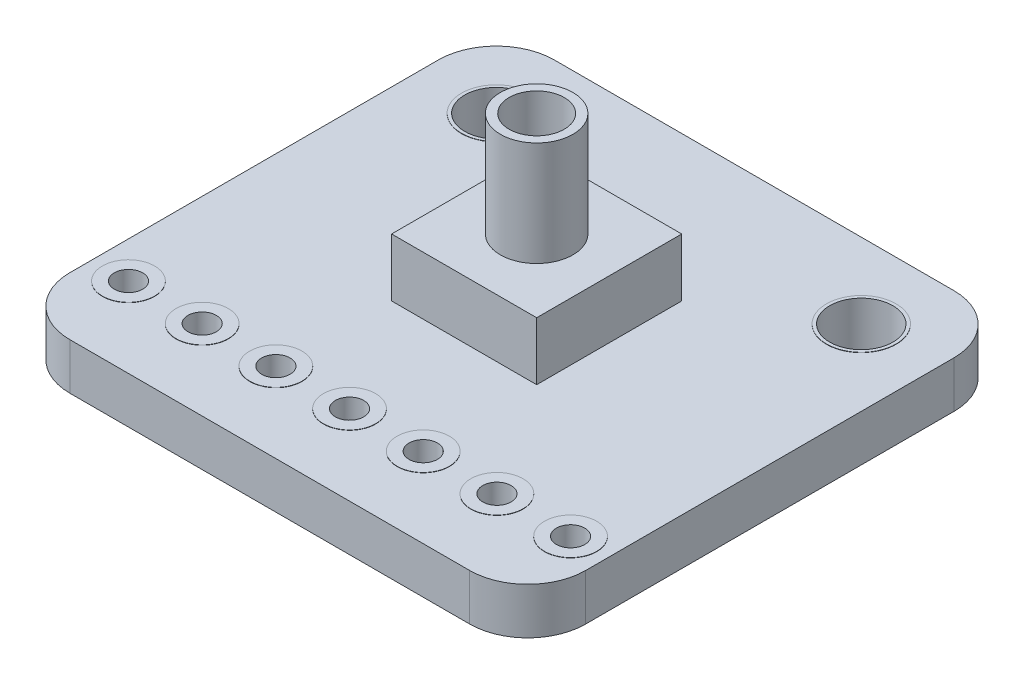
SolidWorks part; units mm, degrees
ref_plane "Front Plane" through (0, 0, 0) normal (0, 0, 1) x (1, 0, 0)
ref_plane "Top Plane" through (0, 0, 0) normal (0, 1, 0) x (1, 0, 0)
ref_plane "Right Plane" through (0, 0, 0) normal (1, 0, 0) x (0, 0, -1)
sketch "Sketch1" plane through (0, 0, 0) normal (0, 1, 0) x (1, 0, 0)
  line L1 (-6.89, 8.35) -> (6.89, 8.35)
  line L2 (-8.89, 6.35) -> (-8.89, -6.35)
  line L3 (-6.89, -8.35) -> (6.89, -8.35)
  line L4 (8.89, 6.35) -> (8.89, -6.35)
  line L5 (-8.89, 8.35) -> (8.89, -8.35) construction
  line L6 (-8.89, -8.35) -> (8.89, 8.35) construction
  arc A0 (-8.89, -6.35) -> (-6.89, -8.35) centre (-6.89, -6.35) ccw
  arc A1 (6.89, -8.35) -> (8.89, -6.35) centre (6.89, -6.35) ccw
  arc A2 (6.89, 8.35) -> (8.89, 6.35) centre (6.89, 6.35) cw
  arc A3 (-6.89, 8.35) -> (-8.89, 6.35) centre (-6.89, 6.35) ccw
  point P0 (0, 0)
  dimension "D3" = 2
  dimension "D1" = 17.78
  dimension "D2" = 16.7
extrude "Boss-Extrude1" add sketch "Sketch1" along normal blind 1.6
sketch "Sketch2" plane through (0, 1.6, 0) normal (0, 1, 0) x (1, 0, 0)
  line L0 (0, 0) -> (0, 8.35) construction
  line L1 (-8.89, -8.35) -> (8.89, 8.35) construction
  line L2 (-6.89, 8.35) -> (6.89, 8.35) construction
  line L3 (-6.89, -8.35) -> (6.89, -8.35) construction
  line L4 (-8.89, -4.33) -> (8.89, -4.33) construction
  line L5 (-8.89, -4.33) -> (-8.89, -6.87) construction
  line L6 (-8.89, -6.87) -> (8.89, -6.87) construction
  line L7 (8.89, -4.33) -> (8.89, -6.87) construction
  line L8 (-8.89, -4.33) -> (8.89, -6.87) construction
  line L9 (-8.89, -6.87) -> (8.89, -4.33) construction
  line L10 (-8.89, 6.35) -> (-8.89, -6.35) construction
  line L11 (8.89, 6.35) -> (8.89, -6.35) construction
  line L12 (6.89, 8.35) -> (-6.89, 8.35) construction
  circle A0 centre (-6.29, 5.75) radius 1.1
  circle A1 centre (6.29, 5.75) radius 1.1
  circle A2 centre (-7.62, -5.6) radius 0.5
  circle A3 centre (-5.08, -5.6) radius 0.5
  circle A4 centre (-2.54, -5.6) radius 0.5
  circle A5 centre (0, -5.6) radius 0.5
  circle A6 centre (2.54, -5.6) radius 0.5
  circle A7 centre (5.08, -5.6) radius 0.5
  circle A8 centre (7.62, -5.6) radius 0.5
  point P2 (-6.89, 6.35)
  point P12 (0, -5.6)
  point P21 (-6.89, 6.35)
  point P22 (-8.89, -5.6)
  point P27 (0, 0)
  point P40 (-6.71, 5.505)
  dimension "D1" = 2.2
  dimension "D5" = 1
  dimension "D2" = 2.75
  dimension "D3" = 2.54
  dimension "D4" = 1.27
  dimension "D7" = 2.54
  dimension "D8" = 2.6
  dimension "D9" = 2.6
  dimension "D6" = 7
extrude "Cut-Extrude1" cut sketch "Sketch2" against normal blind 1.6
ref_plane "Plane1" through (0, 1.61, 0) normal (0, 1, 0) x (1, 0, 0)
sketch "Sketch3" plane through (0, 1.61, 0) normal (0, 1, 0) x (1, 0, 0)
  circle A0 centre (-6.29, 5.75) radius 1.1 construction
  circle A1 centre (-6.29, 5.75) radius 1.1 construction
  circle A2 centre (6.29, 5.75) radius 1.1 construction
  circle A3 centre (6.29, 5.75) radius 1.1 construction
  circle A4 centre (-6.29, 5.75) radius 1.2
  circle A5 centre (6.29, 5.75) radius 1.2
  circle A6 centre (-6.29, 5.75) radius 1.09
  circle A7 centre (6.29, 5.75) radius 1.09
  circle A8 centre (7.62, -5.6) radius 0.5 construction
  circle A9 centre (5.08, -5.6) radius 0.5 construction
  circle A10 centre (2.54, -5.6) radius 0.5 construction
  circle A11 centre (0, -5.6) radius 0.5 construction
  circle A12 centre (-2.54, -5.6) radius 0.5 construction
  circle A13 centre (-5.08, -5.6) radius 0.5 construction
  circle A14 centre (-7.62, -5.6) radius 0.5 construction
  circle A15 centre (7.62, -5.6) radius 0.5 construction
  circle A16 centre (5.08, -5.6) radius 0.5 construction
  circle A17 centre (2.54, -5.6) radius 0.5 construction
  circle A18 centre (0, -5.6) radius 0.5 construction
  circle A19 centre (-2.54, -5.6) radius 0.5 construction
  circle A20 centre (-5.08, -5.6) radius 0.5 construction
  circle A21 centre (-7.62, -5.6) radius 0.5 construction
  circle A22 centre (7.62, -5.6) radius 0.9
  circle A23 centre (5.08, -5.6) radius 0.9
  circle A24 centre (2.54, -5.6) radius 0.9
  circle A25 centre (0, -5.6) radius 0.9
  circle A26 centre (-2.54, -5.6) radius 0.9
  circle A27 centre (-5.08, -5.6) radius 0.9
  circle A28 centre (-7.62, -5.6) radius 0.9
  circle A29 centre (7.62, -5.6) radius 0.49
  circle A30 centre (5.08, -5.6) radius 0.49
  circle A31 centre (2.54, -5.6) radius 0.49
  circle A32 centre (0, -5.6) radius 0.49
  circle A33 centre (-2.54, -5.6) radius 0.49
  circle A34 centre (-5.08, -5.6) radius 0.49
  circle A35 centre (-7.62, -5.6) radius 0.49
  dimension "D1" = 0.1
  dimension "D2" = 0.01
  dimension "D3" = 0.4
  dimension "D4" = 0.01
extrude "Boss-Extrude2" add sketch "Sketch3" against normal offset from surface (1.62 mm away) 0.01 up to face at (-2.54, 0, 6.1) offset beyond the face yes
sketch "Sketch5" plane through (0, 1.6, 0) normal (0, 1, 0) x (1, 0, 0)
  line L0 (-6.89, 8.35) -> (6.89, 8.35) construction
  line L1 (-2.5, 3.35) -> (2.5, 3.35)
  line L2 (-2.5, 3.35) -> (-2.5, -1.65)
  line L3 (-2.5, -1.65) -> (2.5, -1.65)
  line L4 (2.5, 3.35) -> (2.5, -1.65)
  line L5 (-2.5, 3.35) -> (2.5, -1.65) construction
  line L6 (-2.5, -1.65) -> (2.5, 3.35) construction
  point P0 (0, 0.85)
  dimension "D1" = 5
  dimension "D2" = 5
extrude "Boss-Extrude3" add sketch "Sketch5" along normal blind 2
sketch "Sketch6" plane through (0, 3.6, 0) normal (0, 1, 0) x (1, 0, 0)
  line L0 (-2.5, 3.35) -> (2.5, -1.65) construction
  circle A0 centre (0, 0.85) radius 1.25
  circle A2 centre (0, 0.85) radius 0.95
  dimension "D1" = 2.5
  dimension "D2" = 0.3
extrude "Boss-Extrude4" add sketch "Sketch6" along normal blind 3.6
